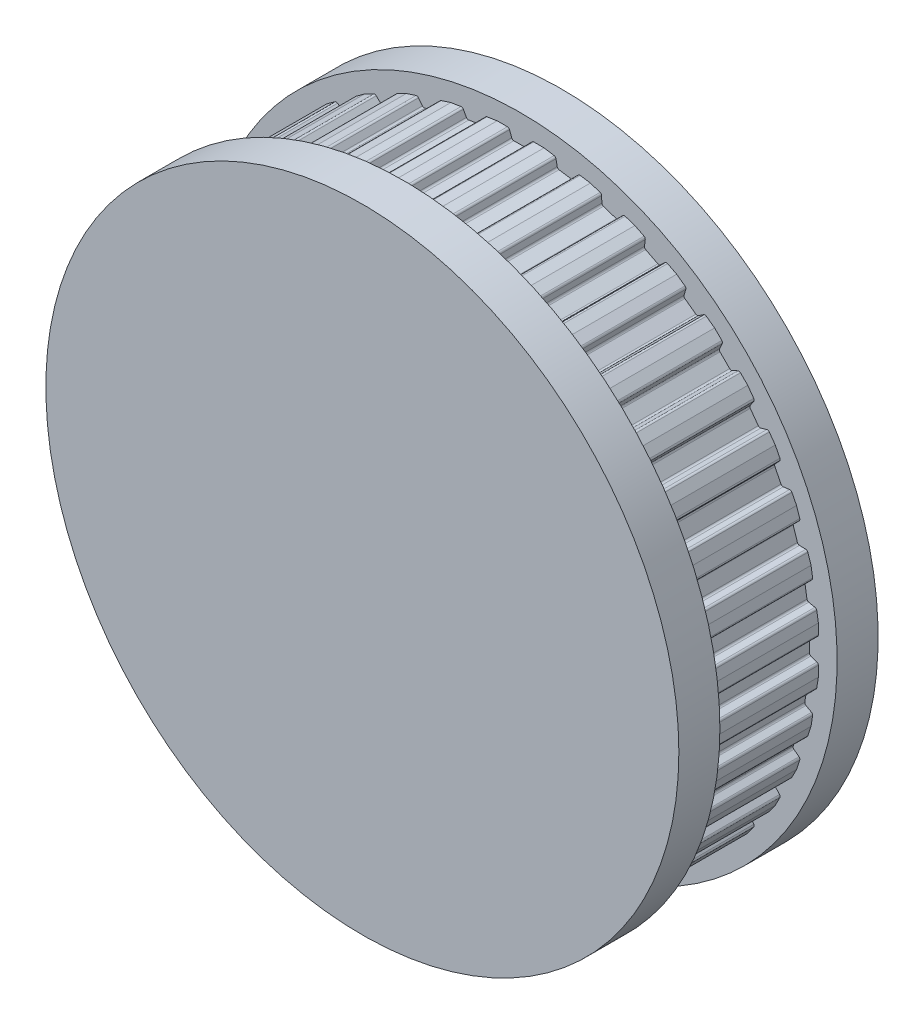
SolidWorks part; units mm, degrees
ref_plane "Front Plane" through (0, 0, 0) normal (0, 0, 1) x (1, 0, 0)
ref_plane "Top Plane" through (0, 0, 0) normal (0, 1, 0) x (1, 0, 0)
ref_plane "Right Plane" through (0, 0, 0) normal (1, 0, 0) x (0, 0, -1)
sketch "Sketch1" plane through (0, 0, 0) normal (0, 0, 1) x (1, 0, 0)
  line L0 (-50.7835, 0) -> (-50.3466, 0)
  line L5 (-50.2571, 0.0627) -> (-50.1641, 0.3183)
  line L6 (-50.0746, 0.381) -> (-49.4934, 0.381)
  line L7 (-49.784, 0.381) -> (-49.784, 0) construction
  line L8 (-49.3109, 0.0627) -> (-49.4039, 0.3183)
  line L39 (-51.2936, 0.1442) -> (-51.3455, 0.4113)
  line L40 (-50.2571, 0.0627) -> (-49.3109, 0.0627) construction
  line L56 (-49.2214, 0) -> (-48.7845, 0)
  line L60 (-51.9981, 0.5781) -> (-51.4241, 0.4872)
  line L61 (-52.2282, 0.2923) -> (-52.0963, 0.5302)
  line L62 (-52.7579, 0.3127) -> (-52.3264, 0.2444)
  line L63 (-51.215, 0.0683) -> (-50.7835, 0)
  line L64 (-53.2392, 0.535) -> (-53.2487, 0.8069)
  line L65 (-53.8671, 1.0737) -> (-53.3144, 0.8941)
  line L66 (-54.1391, 0.8274) -> (-53.9716, 1.0418)
  line L67 (-54.6591, 0.9304) -> (-54.2436, 0.7954)
  line L68 (-53.1734, 0.4477) -> (-52.7579, 0.3127)
  line L69 (-55.0997, 1.2253) -> (-55.0665, 1.4953)
  line L70 (-55.6356, 1.8556) -> (-55.1178, 1.5918)
  line L71 (-55.9428, 1.6549) -> (-55.7438, 1.8404)
  line L72 (-56.4403, 1.838) -> (-56.051, 1.6396)
  line L73 (-55.0484, 1.1288) -> (-54.6591, 0.9304)
  line L74 (-56.8293, 2.1981) -> (-56.7543, 2.4596)
  line L75 (-57.26, 2.9045) -> (-56.7898, 2.5629)
  line L76 (-57.5948, 2.7543) -> (-57.3693, 2.9064)
  line L77 (-58.0575, 3.013) -> (-57.7041, 2.7562)
  line L78 (-56.7937, 2.0948) -> (-56.4403, 1.838)
  line L79 (-58.3854, 3.4295) -> (-58.2704, 3.6761)
  line L80 (-58.7003, 4.1946) -> (-58.2894, 3.7837)
  line L81 (-59.0545, 4.0986) -> (-58.8079, 4.2136)
  line L82 (-59.471, 4.4265) -> (-59.1621, 4.1176)
  line L83 (-58.3664, 3.3219) -> (-58.0575, 3.013)
  line L84 (-59.7297, 4.8892) -> (-59.5776, 5.1147)
  line L85 (-59.9211, 5.6942) -> (-59.5795, 5.224)
  line L86 (-60.2859, 5.6547) -> (-60.0244, 5.7297)
  line L87 (-60.646, 6.0437) -> (-60.3892, 5.6903)
  line L88 (-59.7278, 4.7799) -> (-59.471, 4.4265)
  line L89 (-60.8291, 6.5412) -> (-60.6436, 6.7402)
  line L90 (-60.8922, 7.3662) -> (-60.6284, 6.8484)
  line L91 (-61.2587, 7.3843) -> (-60.9887, 7.4175)
  line L92 (-61.5536, 7.8249) -> (-61.3552, 7.4356)
  line L93 (-60.8444, 6.433) -> (-60.646, 6.0437)
  line L94 (-61.6566, 8.3449) -> (-61.4422, 8.5124)
  line L95 (-61.5899, 9.1696) -> (-61.4103, 8.6169)
  line L96 (-61.949, 9.2448) -> (-61.6771, 9.2353)
  line L97 (-62.1713, 9.7261) -> (-62.0363, 9.3106)
  line L98 (-61.6886, 8.2404) -> (-61.5536, 7.8249)
  line L99 (-62.1917, 10.2558) -> (-61.9538, 10.3877)
  line L100 (-61.9968, 11.0599) -> (-61.9059, 10.4859)
  line L101 (-62.3398, 11.1904) -> (-62.0727, 11.1385)
  line L102 (-62.484, 11.7005) -> (-62.4157, 11.269)
  line L103 (-62.2396, 10.1576) -> (-62.1713, 9.7261)
  line L104 (-62.4213, 12.2269) -> (-62.1657, 12.3199)
  line L105 (-62.103, 12.9906) -> (-62.103, 12.4094)
  line L106 (-62.4213, 13.1731) -> (-62.1657, 13.0801)
  line L107 (-62.484, 13.6995) -> (-62.484, 13.2626)
  line L108 (-62.484, 12.1374) -> (-62.484, 11.7005)
  line L109 (-62.3398, 14.2096) -> (-62.0727, 14.2615)
  line L110 (-61.9059, 14.9141) -> (-61.9968, 14.3401)
  line L111 (-62.1917, 15.1442) -> (-61.9538, 15.0123)
  line L112 (-62.1713, 15.6739) -> (-62.2396, 15.2424)
  line L113 (-62.4157, 14.131) -> (-62.484, 13.6995)
  line L114 (-61.949, 16.1552) -> (-61.6771, 16.1647)
  line L115 (-61.4103, 16.7831) -> (-61.5899, 16.2304)
  line L116 (-61.6566, 17.0551) -> (-61.4422, 16.8876)
  line L117 (-61.5536, 17.5751) -> (-61.6886, 17.1596)
  line L118 (-62.0363, 16.0894) -> (-62.1713, 15.6739)
  line L119 (-61.2587, 18.0157) -> (-60.9887, 17.9825)
  line L120 (-60.6284, 18.5516) -> (-60.8922, 18.0338)
  line L121 (-60.8291, 18.8588) -> (-60.6436, 18.6598)
  line L122 (-60.646, 19.3563) -> (-60.8444, 18.967)
  line L123 (-61.3552, 17.9644) -> (-61.5536, 17.5751)
  line L124 (-60.2859, 19.7453) -> (-60.0244, 19.6703)
  line L125 (-59.5795, 20.176) -> (-59.9211, 19.7058)
  line L126 (-59.7297, 20.5108) -> (-59.5776, 20.2853)
  line L127 (-59.471, 20.9735) -> (-59.7278, 20.6201)
  line L128 (-60.3892, 19.7097) -> (-60.646, 19.3563)
  line L129 (-59.0545, 21.3014) -> (-58.8079, 21.1864)
  line L130 (-58.2894, 21.6163) -> (-58.7003, 21.2054)
  line L131 (-58.3854, 21.9705) -> (-58.2704, 21.7239)
  line L132 (-58.0575, 22.387) -> (-58.3664, 22.0781)
  line L133 (-59.1621, 21.2824) -> (-59.471, 20.9735)
  line L134 (-57.5948, 22.6457) -> (-57.3693, 22.4936)
  line L135 (-56.7898, 22.8371) -> (-57.26, 22.4955)
  line L136 (-56.8293, 23.2019) -> (-56.7543, 22.9404)
  line L137 (-56.4403, 23.562) -> (-56.7937, 23.3052)
  line L138 (-57.7041, 22.6438) -> (-58.0575, 22.387)
  line L139 (-55.9428, 23.7451) -> (-55.7438, 23.5596)
  line L140 (-55.1178, 23.8082) -> (-55.6356, 23.5444)
  line L141 (-55.0997, 24.1747) -> (-55.0665, 23.9047)
  line L142 (-54.6591, 24.4696) -> (-55.0484, 24.2712)
  line L143 (-56.051, 23.7604) -> (-56.4403, 23.562)
  line L144 (-54.1391, 24.5726) -> (-53.9716, 24.3582)
  line L145 (-53.3144, 24.5059) -> (-53.8671, 24.3263)
  line L146 (-53.2392, 24.865) -> (-53.2487, 24.5931)
  line L147 (-52.7579, 25.0873) -> (-53.1734, 24.9523)
  line L148 (-54.2436, 24.6046) -> (-54.6591, 24.4696)
  line L149 (-52.2282, 25.1077) -> (-52.0963, 24.8698)
  line L150 (-51.4241, 24.9128) -> (-51.9981, 24.8219)
  line L151 (-51.2936, 25.2558) -> (-51.3455, 24.9887)
  line L152 (-50.7835, 25.4) -> (-51.215, 25.3317)
  line L153 (-52.3264, 25.1556) -> (-52.7579, 25.0873)
  line L154 (-50.2571, 25.3373) -> (-50.1641, 25.0817)
  line L155 (-49.4934, 25.019) -> (-50.0746, 25.019)
  line L156 (-49.3109, 25.3373) -> (-49.4039, 25.0817)
  line L157 (-48.7845, 25.4) -> (-49.2214, 25.4)
  line L158 (-50.3466, 25.4) -> (-50.7835, 25.4)
  line L159 (-48.2744, 25.2558) -> (-48.2225, 24.9887)
  line L160 (-47.5699, 24.8219) -> (-48.1439, 24.9128)
  line L161 (-47.3398, 25.1077) -> (-47.4717, 24.8698)
  line L162 (-46.8101, 25.0873) -> (-47.2416, 25.1556)
  line L163 (-48.353, 25.3317) -> (-48.7845, 25.4)
  line L164 (-46.3288, 24.865) -> (-46.3193, 24.5931)
  line L165 (-45.7009, 24.3263) -> (-46.2536, 24.5059)
  line L166 (-45.4289, 24.5726) -> (-45.5964, 24.3582)
  line L167 (-44.9089, 24.4696) -> (-45.3244, 24.6046)
  line L168 (-46.3946, 24.9523) -> (-46.8101, 25.0873)
  line L169 (-44.4683, 24.1747) -> (-44.5015, 23.9047)
  line L170 (-43.9324, 23.5444) -> (-44.4502, 23.8082)
  line L171 (-43.6252, 23.7451) -> (-43.8242, 23.5596)
  line L172 (-43.1277, 23.562) -> (-43.517, 23.7604)
  line L173 (-44.5196, 24.2712) -> (-44.9089, 24.4696)
  line L174 (-42.7387, 23.2019) -> (-42.8137, 22.9404)
  line L175 (-42.308, 22.4955) -> (-42.7782, 22.8371)
  line L176 (-41.9732, 22.6457) -> (-42.1987, 22.4936)
  line L177 (-41.5105, 22.387) -> (-41.8639, 22.6438)
  line L178 (-42.7743, 23.3052) -> (-43.1277, 23.562)
  line L179 (-41.1826, 21.9705) -> (-41.2976, 21.7239)
  line L180 (-40.8677, 21.2054) -> (-41.2786, 21.6163)
  line L181 (-40.5135, 21.3014) -> (-40.7601, 21.1864)
  line L182 (-40.097, 20.9735) -> (-40.4059, 21.2824)
  line L183 (-41.2016, 22.0781) -> (-41.5105, 22.387)
  line L184 (-39.8383, 20.5108) -> (-39.9904, 20.2853)
  line L185 (-39.6469, 19.7058) -> (-39.9885, 20.176)
  line L186 (-39.2821, 19.7453) -> (-39.5436, 19.6703)
  line L187 (-38.922, 19.3563) -> (-39.1788, 19.7097)
  line L188 (-39.8402, 20.6201) -> (-40.097, 20.9735)
  line L189 (-38.7389, 18.8588) -> (-38.9244, 18.6598)
  line L190 (-38.6758, 18.0338) -> (-38.9396, 18.5516)
  line L191 (-38.3093, 18.0157) -> (-38.5793, 17.9825)
  line L192 (-38.0144, 17.5751) -> (-38.2128, 17.9644)
  line L193 (-38.7236, 18.967) -> (-38.922, 19.3563)
  line L194 (-37.9114, 17.0551) -> (-38.1258, 16.8876)
  line L195 (-37.9781, 16.2304) -> (-38.1577, 16.7831)
  line L196 (-37.619, 16.1552) -> (-37.8909, 16.1647)
  line L197 (-37.3967, 15.6739) -> (-37.5317, 16.0894)
  line L198 (-37.8794, 17.1596) -> (-38.0144, 17.5751)
  line L199 (-37.3763, 15.1442) -> (-37.6142, 15.0123)
  line L200 (-37.5712, 14.3401) -> (-37.6621, 14.9141)
  line L201 (-37.2282, 14.2096) -> (-37.4953, 14.2615)
  line L202 (-37.084, 13.6995) -> (-37.1523, 14.131)
  line L203 (-37.3284, 15.2424) -> (-37.3967, 15.6739)
  line L204 (-37.1467, 13.1731) -> (-37.4023, 13.0801)
  line L205 (-37.465, 12.4094) -> (-37.465, 12.9906)
  line L206 (-37.1467, 12.2269) -> (-37.4023, 12.3199)
  line L207 (-37.084, 11.7005) -> (-37.084, 12.1374)
  line L208 (-37.084, 13.2626) -> (-37.084, 13.6995)
  line L209 (-37.2282, 11.1904) -> (-37.4953, 11.1385)
  line L210 (-37.6621, 10.4859) -> (-37.5712, 11.0599)
  line L211 (-37.3763, 10.2558) -> (-37.6142, 10.3877)
  line L212 (-37.3967, 9.7261) -> (-37.3284, 10.1576)
  line L213 (-37.1523, 11.269) -> (-37.084, 11.7005)
  line L214 (-37.619, 9.2448) -> (-37.8909, 9.2353)
  line L215 (-38.1577, 8.6169) -> (-37.9781, 9.1696)
  line L216 (-37.9114, 8.3449) -> (-38.1258, 8.5124)
  line L217 (-38.0144, 7.8249) -> (-37.8794, 8.2404)
  line L218 (-37.5317, 9.3106) -> (-37.3967, 9.7261)
  line L219 (-38.3093, 7.3843) -> (-38.5793, 7.4175)
  line L220 (-38.9396, 6.8484) -> (-38.6758, 7.3662)
  line L221 (-38.7389, 6.5412) -> (-38.9244, 6.7402)
  line L222 (-38.922, 6.0437) -> (-38.7236, 6.433)
  line L223 (-38.2128, 7.4356) -> (-38.0144, 7.8249)
  line L224 (-39.2821, 5.6547) -> (-39.5436, 5.7297)
  line L225 (-39.9885, 5.224) -> (-39.6469, 5.6942)
  line L226 (-39.8383, 4.8892) -> (-39.9904, 5.1147)
  line L227 (-40.097, 4.4265) -> (-39.8402, 4.7799)
  line L228 (-39.1788, 5.6903) -> (-38.922, 6.0437)
  line L229 (-40.5135, 4.0986) -> (-40.7601, 4.2136)
  line L230 (-41.2786, 3.7837) -> (-40.8677, 4.1946)
  line L231 (-41.1826, 3.4295) -> (-41.2976, 3.6761)
  line L232 (-41.5105, 3.013) -> (-41.2016, 3.3219)
  line L233 (-40.4059, 4.1176) -> (-40.097, 4.4265)
  line L234 (-41.9732, 2.7543) -> (-42.1987, 2.9064)
  line L235 (-42.7782, 2.5629) -> (-42.308, 2.9045)
  line L236 (-42.7387, 2.1981) -> (-42.8137, 2.4596)
  line L237 (-43.1277, 1.838) -> (-42.7743, 2.0948)
  line L238 (-41.8639, 2.7562) -> (-41.5105, 3.013)
  line L239 (-43.6252, 1.6549) -> (-43.8242, 1.8404)
  line L240 (-44.4502, 1.5918) -> (-43.9324, 1.8556)
  line L241 (-44.4683, 1.2253) -> (-44.5015, 1.4953)
  line L242 (-44.9089, 0.9304) -> (-44.5196, 1.1288)
  line L243 (-43.517, 1.6396) -> (-43.1277, 1.838)
  line L244 (-45.4289, 0.8274) -> (-45.5964, 1.0418)
  line L245 (-46.2536, 0.8941) -> (-45.7009, 1.0737)
  line L246 (-46.3288, 0.535) -> (-46.3193, 0.8069)
  line L247 (-46.8101, 0.3127) -> (-46.3946, 0.4477)
  line L248 (-45.3244, 0.7954) -> (-44.9089, 0.9304)
  line L249 (-47.3398, 0.2923) -> (-47.4717, 0.5302)
  line L250 (-48.1439, 0.4872) -> (-47.5699, 0.5781)
  line L251 (-48.2744, 0.1442) -> (-48.2225, 0.4113)
  line L252 (-48.7845, 0) -> (-48.353, 0.0683)
  line L253 (-47.2416, 0.2444) -> (-46.8101, 0.3127)
  arc A0 (-50.3466, 0) -> (-50.2571, 0.0627) centre (-50.3466, 0.0952) ccw
  arc A1 (-50.1641, 0.3183) -> (-50.0746, 0.381) centre (-50.0746, 0.2857) cw
  arc A2 (-49.4039, 0.3183) -> (-49.4934, 0.381) centre (-49.4934, 0.2857) ccw
  arc A3 (-49.2214, 0) -> (-49.3109, 0.0627) centre (-49.2214, 0.0952) cw
  arc A4 (-51.215, 0.0683) -> (-51.2936, 0.1442) centre (-51.2001, 0.1624) cw
  arc A5 (-51.3455, 0.4113) -> (-51.4241, 0.4872) centre (-51.439, 0.3931) ccw
  arc A6 (-52.0963, 0.5302) -> (-51.9981, 0.5781) centre (-52.013, 0.484) cw
  arc A7 (-52.3264, 0.2444) -> (-52.2282, 0.2923) centre (-52.3115, 0.3385) ccw
  arc A8 (-53.1734, 0.4477) -> (-53.2392, 0.535) centre (-53.144, 0.5383) cw
  arc A9 (-53.2487, 0.8069) -> (-53.3144, 0.8941) centre (-53.3439, 0.8036) ccw
  arc A10 (-53.9716, 1.0418) -> (-53.8671, 1.0737) centre (-53.8966, 0.9831) cw
  arc A11 (-54.2436, 0.7954) -> (-54.1391, 0.8274) centre (-54.2142, 0.886) ccw
  arc A12 (-55.0484, 1.1288) -> (-55.0997, 1.2253) centre (-55.0051, 1.2137) cw
  arc A13 (-55.0665, 1.4953) -> (-55.1178, 1.5918) centre (-55.1611, 1.5069) ccw
  arc A14 (-55.7438, 1.8404) -> (-55.6356, 1.8556) centre (-55.6789, 1.7707) cw
  arc A15 (-56.051, 1.6396) -> (-55.9428, 1.6549) centre (-56.0077, 1.7245) ccw
  arc A16 (-56.7937, 2.0948) -> (-56.8293, 2.1981) centre (-56.7377, 2.1718) cw
  arc A17 (-56.7543, 2.4596) -> (-56.7898, 2.5629) centre (-56.8458, 2.4859) ccw
  arc A18 (-57.3693, 2.9064) -> (-57.26, 2.9045) centre (-57.316, 2.8275) cw
  arc A19 (-57.7041, 2.7562) -> (-57.5948, 2.7543) centre (-57.6481, 2.8333) ccw
  arc A20 (-58.3664, 3.3219) -> (-58.3854, 3.4295) centre (-58.2991, 3.3893) cw
  arc A21 (-58.2704, 3.6761) -> (-58.2894, 3.7837) centre (-58.3567, 3.7163) ccw
  arc A22 (-58.8079, 4.2136) -> (-58.7003, 4.1946) centre (-58.7677, 4.1273) cw
  arc A23 (-59.1621, 4.1176) -> (-59.0545, 4.0986) centre (-59.0947, 4.1849) ccw
  arc A24 (-59.7278, 4.7799) -> (-59.7297, 4.8892) centre (-59.6507, 4.8359) cw
  arc A25 (-59.5776, 5.1147) -> (-59.5795, 5.224) centre (-59.6565, 5.168) ccw
  arc A26 (-60.0244, 5.7297) -> (-59.9211, 5.6942) centre (-59.9981, 5.6382) cw
  arc A27 (-60.3892, 5.6903) -> (-60.2859, 5.6547) centre (-60.3122, 5.7463) ccw
  arc A28 (-60.8444, 6.433) -> (-60.8291, 6.5412) centre (-60.7595, 6.4763) cw
  arc A29 (-60.6436, 6.7402) -> (-60.6284, 6.8484) centre (-60.7133, 6.8051) ccw
  arc A30 (-60.9887, 7.4175) -> (-60.8922, 7.3662) centre (-60.9771, 7.3229) cw
  arc A31 (-61.3552, 7.4356) -> (-61.2587, 7.3843) centre (-61.2703, 7.4789) ccw
  arc A32 (-61.6886, 8.2404) -> (-61.6566, 8.3449) centre (-61.598, 8.2698) cw
  arc A33 (-61.4422, 8.5124) -> (-61.4103, 8.6169) centre (-61.5009, 8.5874) ccw
  arc A34 (-61.6771, 9.2353) -> (-61.5899, 9.1696) centre (-61.6804, 9.1401) cw
  arc A35 (-62.0363, 9.3106) -> (-61.949, 9.2448) centre (-61.9457, 9.34) ccw
  arc A36 (-62.2396, 10.1576) -> (-62.1917, 10.2558) centre (-62.1455, 10.1725) cw
  arc A37 (-61.9538, 10.3877) -> (-61.9059, 10.4859) centre (-62, 10.471) ccw
  arc A38 (-62.0727, 11.1385) -> (-61.9968, 11.0599) centre (-62.0909, 11.045) cw
  arc A39 (-62.4157, 11.269) -> (-62.3398, 11.1904) centre (-62.3216, 11.2839) ccw
  arc A40 (-62.484, 12.1374) -> (-62.4213, 12.2269) centre (-62.3888, 12.1374) cw
  arc A41 (-62.1657, 12.3199) -> (-62.103, 12.4094) centre (-62.1983, 12.4094) ccw
  arc A42 (-62.1657, 13.0801) -> (-62.103, 12.9906) centre (-62.1983, 12.9906) cw
  arc A43 (-62.484, 13.2626) -> (-62.4213, 13.1731) centre (-62.3888, 13.2626) ccw
  arc A44 (-62.4157, 14.131) -> (-62.3398, 14.2096) centre (-62.3216, 14.1161) cw
  arc A45 (-62.0727, 14.2615) -> (-61.9968, 14.3401) centre (-62.0909, 14.355) ccw
  arc A46 (-61.9538, 15.0123) -> (-61.9059, 14.9141) centre (-62, 14.929) cw
  arc A47 (-62.2396, 15.2424) -> (-62.1917, 15.1442) centre (-62.1455, 15.2275) ccw
  arc A48 (-62.0363, 16.0894) -> (-61.949, 16.1552) centre (-61.9457, 16.06) cw
  arc A49 (-61.6771, 16.1647) -> (-61.5899, 16.2304) centre (-61.6804, 16.2599) ccw
  arc A50 (-61.4422, 16.8876) -> (-61.4103, 16.7831) centre (-61.5009, 16.8126) cw
  arc A51 (-61.6886, 17.1596) -> (-61.6566, 17.0551) centre (-61.598, 17.1302) ccw
  arc A52 (-61.3552, 17.9644) -> (-61.2587, 18.0157) centre (-61.2703, 17.9211) cw
  arc A53 (-60.9887, 17.9825) -> (-60.8922, 18.0338) centre (-60.9771, 18.0771) ccw
  arc A54 (-60.6436, 18.6598) -> (-60.6284, 18.5516) centre (-60.7133, 18.5949) cw
  arc A55 (-60.8444, 18.967) -> (-60.8291, 18.8588) centre (-60.7595, 18.9237) ccw
  arc A56 (-60.3892, 19.7097) -> (-60.2859, 19.7453) centre (-60.3122, 19.6537) cw
  arc A57 (-60.0244, 19.6703) -> (-59.9211, 19.7058) centre (-59.9981, 19.7618) ccw
  arc A58 (-59.5776, 20.2853) -> (-59.5795, 20.176) centre (-59.6565, 20.232) cw
  arc A59 (-59.7278, 20.6201) -> (-59.7297, 20.5108) centre (-59.6507, 20.5641) ccw
  arc A60 (-59.1621, 21.2824) -> (-59.0545, 21.3014) centre (-59.0947, 21.2151) cw
  arc A61 (-58.8079, 21.1864) -> (-58.7003, 21.2054) centre (-58.7677, 21.2727) ccw
  arc A62 (-58.2704, 21.7239) -> (-58.2894, 21.6163) centre (-58.3567, 21.6837) cw
  arc A63 (-58.3664, 22.0781) -> (-58.3854, 21.9705) centre (-58.2991, 22.0107) ccw
  arc A64 (-57.7041, 22.6438) -> (-57.5948, 22.6457) centre (-57.6481, 22.5667) cw
  arc A65 (-57.3693, 22.4936) -> (-57.26, 22.4955) centre (-57.316, 22.5725) ccw
  arc A66 (-56.7543, 22.9404) -> (-56.7898, 22.8371) centre (-56.8458, 22.9141) cw
  arc A67 (-56.7937, 23.3052) -> (-56.8293, 23.2019) centre (-56.7377, 23.2282) ccw
  arc A68 (-56.051, 23.7604) -> (-55.9428, 23.7451) centre (-56.0077, 23.6755) cw
  arc A69 (-55.7438, 23.5596) -> (-55.6356, 23.5444) centre (-55.6789, 23.6293) ccw
  arc A70 (-55.0665, 23.9047) -> (-55.1178, 23.8082) centre (-55.1611, 23.8931) cw
  arc A71 (-55.0484, 24.2712) -> (-55.0997, 24.1747) centre (-55.0051, 24.1863) ccw
  arc A72 (-54.2436, 24.6046) -> (-54.1391, 24.5726) centre (-54.2142, 24.514) cw
  arc A73 (-53.9716, 24.3582) -> (-53.8671, 24.3263) centre (-53.8966, 24.4169) ccw
  arc A74 (-53.2487, 24.5931) -> (-53.3144, 24.5059) centre (-53.3439, 24.5964) cw
  arc A75 (-53.1734, 24.9523) -> (-53.2392, 24.865) centre (-53.144, 24.8617) ccw
  arc A76 (-52.3264, 25.1556) -> (-52.2282, 25.1077) centre (-52.3115, 25.0615) cw
  arc A77 (-52.0963, 24.8698) -> (-51.9981, 24.8219) centre (-52.013, 24.916) ccw
  arc A78 (-51.3455, 24.9887) -> (-51.4241, 24.9128) centre (-51.439, 25.0069) cw
  arc A79 (-51.215, 25.3317) -> (-51.2936, 25.2558) centre (-51.2001, 25.2376) ccw
  arc A80 (-50.3466, 25.4) -> (-50.2571, 25.3373) centre (-50.3466, 25.3048) cw
  arc A81 (-50.1641, 25.0817) -> (-50.0746, 25.019) centre (-50.0746, 25.1143) ccw
  arc A82 (-49.4039, 25.0817) -> (-49.4934, 25.019) centre (-49.4934, 25.1143) cw
  arc A83 (-49.2214, 25.4) -> (-49.3109, 25.3373) centre (-49.2214, 25.3048) ccw
  arc A84 (-48.353, 25.3317) -> (-48.2744, 25.2558) centre (-48.3679, 25.2376) cw
  arc A85 (-48.2225, 24.9887) -> (-48.1439, 24.9128) centre (-48.129, 25.0069) ccw
  arc A86 (-47.4717, 24.8698) -> (-47.5699, 24.8219) centre (-47.555, 24.916) cw
  arc A87 (-47.2416, 25.1556) -> (-47.3398, 25.1077) centre (-47.2565, 25.0615) ccw
  arc A88 (-46.3946, 24.9523) -> (-46.3288, 24.865) centre (-46.424, 24.8617) cw
  arc A89 (-46.3193, 24.5931) -> (-46.2536, 24.5059) centre (-46.2241, 24.5964) ccw
  arc A90 (-45.5964, 24.3582) -> (-45.7009, 24.3263) centre (-45.6714, 24.4169) cw
  arc A91 (-45.3244, 24.6046) -> (-45.4289, 24.5726) centre (-45.3538, 24.514) ccw
  arc A92 (-44.5196, 24.2712) -> (-44.4683, 24.1747) centre (-44.5629, 24.1863) cw
  arc A93 (-44.5015, 23.9047) -> (-44.4502, 23.8082) centre (-44.4069, 23.8931) ccw
  arc A94 (-43.8242, 23.5596) -> (-43.9324, 23.5444) centre (-43.8891, 23.6293) cw
  arc A95 (-43.517, 23.7604) -> (-43.6252, 23.7451) centre (-43.5603, 23.6755) ccw
  arc A96 (-42.7743, 23.3052) -> (-42.7387, 23.2019) centre (-42.8303, 23.2282) cw
  arc A97 (-42.8137, 22.9404) -> (-42.7782, 22.8371) centre (-42.7222, 22.9141) ccw
  arc A98 (-42.1987, 22.4936) -> (-42.308, 22.4955) centre (-42.252, 22.5725) cw
  arc A99 (-41.8639, 22.6438) -> (-41.9732, 22.6457) centre (-41.9199, 22.5667) ccw
  arc A100 (-41.2016, 22.0781) -> (-41.1826, 21.9705) centre (-41.2689, 22.0107) cw
  arc A101 (-41.2976, 21.7239) -> (-41.2786, 21.6163) centre (-41.2113, 21.6837) ccw
  arc A102 (-40.7601, 21.1864) -> (-40.8677, 21.2054) centre (-40.8003, 21.2727) cw
  arc A103 (-40.4059, 21.2824) -> (-40.5135, 21.3014) centre (-40.4733, 21.2151) ccw
  arc A104 (-39.8402, 20.6201) -> (-39.8383, 20.5108) centre (-39.9173, 20.5641) cw
  arc A105 (-39.9904, 20.2853) -> (-39.9885, 20.176) centre (-39.9115, 20.232) ccw
  arc A106 (-39.5436, 19.6703) -> (-39.6469, 19.7058) centre (-39.5699, 19.7618) cw
  arc A107 (-39.1788, 19.7097) -> (-39.2821, 19.7453) centre (-39.2558, 19.6537) ccw
  arc A108 (-38.7236, 18.967) -> (-38.7389, 18.8588) centre (-38.8085, 18.9237) cw
  arc A109 (-38.9244, 18.6598) -> (-38.9396, 18.5516) centre (-38.8547, 18.5949) ccw
  arc A110 (-38.5793, 17.9825) -> (-38.6758, 18.0338) centre (-38.5909, 18.0771) cw
  arc A111 (-38.2128, 17.9644) -> (-38.3093, 18.0157) centre (-38.2977, 17.9211) ccw
  arc A112 (-37.8794, 17.1596) -> (-37.9114, 17.0551) centre (-37.97, 17.1302) cw
  arc A113 (-38.1258, 16.8876) -> (-38.1577, 16.7831) centre (-38.0671, 16.8126) ccw
  arc A114 (-37.8909, 16.1647) -> (-37.9781, 16.2304) centre (-37.8876, 16.2599) cw
  arc A115 (-37.5317, 16.0894) -> (-37.619, 16.1552) centre (-37.6223, 16.06) ccw
  arc A116 (-37.3284, 15.2424) -> (-37.3763, 15.1442) centre (-37.4225, 15.2275) cw
  arc A117 (-37.6142, 15.0123) -> (-37.6621, 14.9141) centre (-37.568, 14.929) ccw
  arc A118 (-37.4953, 14.2615) -> (-37.5712, 14.3401) centre (-37.4771, 14.355) cw
  arc A119 (-37.1523, 14.131) -> (-37.2282, 14.2096) centre (-37.2464, 14.1161) ccw
  arc A120 (-37.084, 13.2626) -> (-37.1467, 13.1731) centre (-37.1792, 13.2626) cw
  arc A121 (-37.4023, 13.0801) -> (-37.465, 12.9906) centre (-37.3697, 12.9906) ccw
  arc A122 (-37.4023, 12.3199) -> (-37.465, 12.4094) centre (-37.3698, 12.4094) cw
  arc A123 (-37.084, 12.1374) -> (-37.1467, 12.2269) centre (-37.1792, 12.1374) ccw
  arc A124 (-37.1523, 11.269) -> (-37.2282, 11.1904) centre (-37.2464, 11.2839) cw
  arc A125 (-37.4953, 11.1385) -> (-37.5712, 11.0599) centre (-37.4771, 11.045) ccw
  arc A126 (-37.6142, 10.3877) -> (-37.6621, 10.4859) centre (-37.568, 10.471) cw
  arc A127 (-37.3284, 10.1576) -> (-37.3763, 10.2558) centre (-37.4225, 10.1725) ccw
  arc A128 (-37.5317, 9.3106) -> (-37.619, 9.2448) centre (-37.6223, 9.34) cw
  arc A129 (-37.8909, 9.2353) -> (-37.9781, 9.1696) centre (-37.8876, 9.1401) ccw
  arc A130 (-38.1258, 8.5124) -> (-38.1577, 8.6169) centre (-38.0671, 8.5874) cw
  arc A131 (-37.8794, 8.2404) -> (-37.9114, 8.3449) centre (-37.97, 8.2698) ccw
  arc A132 (-38.2128, 7.4356) -> (-38.3093, 7.3843) centre (-38.2977, 7.4789) cw
  arc A133 (-38.5793, 7.4175) -> (-38.6758, 7.3662) centre (-38.5909, 7.3229) ccw
  arc A134 (-38.9244, 6.7402) -> (-38.9396, 6.8484) centre (-38.8547, 6.8051) cw
  arc A135 (-38.7236, 6.433) -> (-38.7389, 6.5412) centre (-38.8085, 6.4763) ccw
  arc A136 (-39.1788, 5.6903) -> (-39.2821, 5.6547) centre (-39.2558, 5.7463) cw
  arc A137 (-39.5436, 5.7297) -> (-39.6469, 5.6942) centre (-39.5699, 5.6382) ccw
  arc A138 (-39.9904, 5.1147) -> (-39.9885, 5.224) centre (-39.9115, 5.168) cw
  arc A139 (-39.8402, 4.7799) -> (-39.8383, 4.8892) centre (-39.9173, 4.8359) ccw
  arc A140 (-40.4059, 4.1176) -> (-40.5135, 4.0986) centre (-40.4733, 4.1849) cw
  arc A141 (-40.7601, 4.2136) -> (-40.8677, 4.1946) centre (-40.8003, 4.1273) ccw
  arc A142 (-41.2976, 3.6761) -> (-41.2786, 3.7837) centre (-41.2113, 3.7163) cw
  arc A143 (-41.2016, 3.3219) -> (-41.1826, 3.4295) centre (-41.2689, 3.3893) ccw
  arc A144 (-41.8639, 2.7562) -> (-41.9732, 2.7543) centre (-41.9199, 2.8333) cw
  arc A145 (-42.1987, 2.9064) -> (-42.308, 2.9045) centre (-42.252, 2.8275) ccw
  arc A146 (-42.8137, 2.4596) -> (-42.7782, 2.5629) centre (-42.7222, 2.4859) cw
  arc A147 (-42.7743, 2.0948) -> (-42.7387, 2.1981) centre (-42.8303, 2.1718) ccw
  arc A148 (-43.517, 1.6396) -> (-43.6252, 1.6549) centre (-43.5603, 1.7245) cw
  arc A149 (-43.8242, 1.8404) -> (-43.9324, 1.8556) centre (-43.8891, 1.7707) ccw
  arc A150 (-44.5015, 1.4953) -> (-44.4502, 1.5918) centre (-44.4069, 1.5069) cw
  arc A151 (-44.5196, 1.1288) -> (-44.4683, 1.2253) centre (-44.5629, 1.2137) ccw
  arc A152 (-45.3244, 0.7954) -> (-45.4289, 0.8274) centre (-45.3538, 0.886) cw
  arc A153 (-45.5964, 1.0418) -> (-45.7009, 1.0737) centre (-45.6714, 0.9831) ccw
  arc A154 (-46.3193, 0.8069) -> (-46.2536, 0.8941) centre (-46.2241, 0.8036) cw
  arc A155 (-46.3946, 0.4477) -> (-46.3288, 0.535) centre (-46.424, 0.5383) ccw
  arc A156 (-47.2416, 0.2444) -> (-47.3398, 0.2923) centre (-47.2565, 0.3385) cw
  arc A157 (-47.4717, 0.5302) -> (-47.5699, 0.5781) centre (-47.555, 0.484) ccw
  arc A158 (-48.2225, 0.4113) -> (-48.1439, 0.4872) centre (-48.129, 0.3931) cw
  arc A159 (-48.353, 0.0683) -> (-48.2744, 0.1442) centre (-48.3679, 0.1624) ccw
  point P1 (-50.292, 0.0172)
  point P2 (-49.784, 12.7)
  point P7 (-49.276, 0.0172)
  point P570 (-49.784, 12.7)
  dimension "D1" = 0.0953
  dimension "D2" = 40
  dimension "D3" = 40
  dimension "D4" = 1.016
  dimension "D7" = 0.381
sketch "Sketch2" plane through (0, 0, 0) normal (0, 0, 1) x (1, 0, 0)
  point P0 (-49.784, 12.7)
extrude "Boss-Extrude1" add sketch "Sketch1" along normal blind 5
sketch "Sketch3" plane through (0, 0, 5) normal (0, 0, 1) x (1, 0, 0)
  circle A0 centre (-49.784, 12.7) radius 13.5
extrude "Boss-Extrude2" add sketch "Sketch3" along normal blind 1.75
sketch "Sketch4" plane through (0, 0, 0) normal (0, 0, -1) x (-1, 0, 0)
  circle A0 centre (49.784, 12.7) radius 13.5
extrude "Boss-Extrude3" add sketch "Sketch4" along normal blind 1.75
